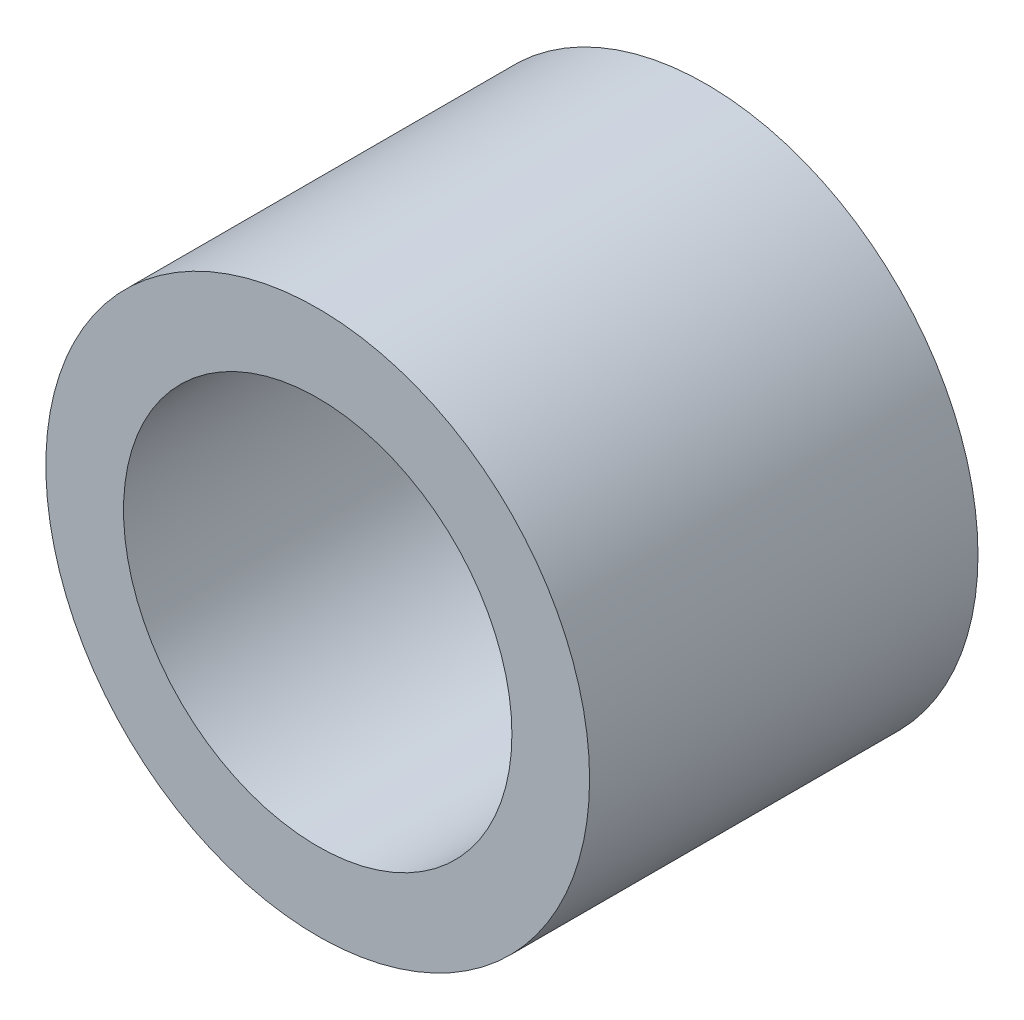
SolidWorks part; units mm, degrees
ref_plane "Front Plane" through (0, 0, 0) normal (0, 0, 1) x (1, 0, 0)
ref_plane "Top Plane" through (0, 0, 0) normal (0, 1, 0) x (1, 0, 0)
ref_plane "Right Plane" through (0, 0, 0) normal (1, 0, 0) x (0, 0, -1)
sketch "Sketch1" plane through (0, 0, 0) normal (0, 0, 1) x (1, 0, 0)
  circle A0 centre (0, 0) radius 4.445
  circle A1 centre (0, 0) radius 3.175
  dimension "D1" = 8.89
  dimension "D2" = 6.35
extrude "Boss-Extrude1" add sketch "Sketch1" along normal blind 6.35
